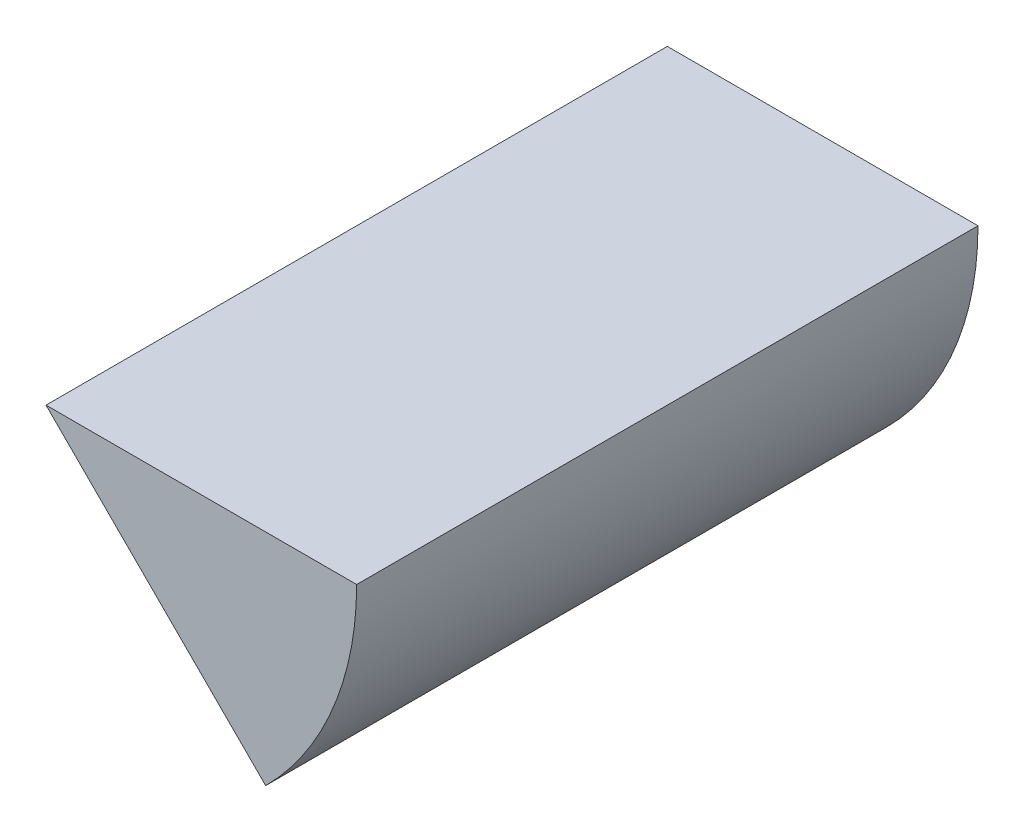
SolidWorks part; units mm, degrees
ref_plane "Alzado" through (0, 0, 0) normal (0, 0, 1) x (1, 0, 0)
ref_plane "Planta" through (0, 0, 0) normal (0, 1, 0) x (1, 0, 0)
ref_plane "Vista lateral" through (0, 0, 0) normal (1, 0, 0) x (0, 0, -1)
sketch "Croquis1" plane through (0, 0, 0) normal (0, 0, 1) x (1, 0, 0)
  line L1 (25, 0) -> (0, 0)
  line L2 (0, 0) -> (17.6777, -17.6777)
  arc A0 (17.6777, -17.6777) -> (25, 0) centre (0, 0) ccw
  dimension "D1" = 50
extrude "Saliente-Extruir1" add sketch "Croquis1" along normal blind 50
sketch "Croquis2" plane through (0, 0, 0) normal (0, 0, -1) x (-1, 0, 0)
  circle A0 centre (-16.7351, -6.6456) radius 5
  dimension "D1" = 10
extrude "Cortar-Extruir1" cut sketch "Croquis2" against normal blind 10 contours A0
